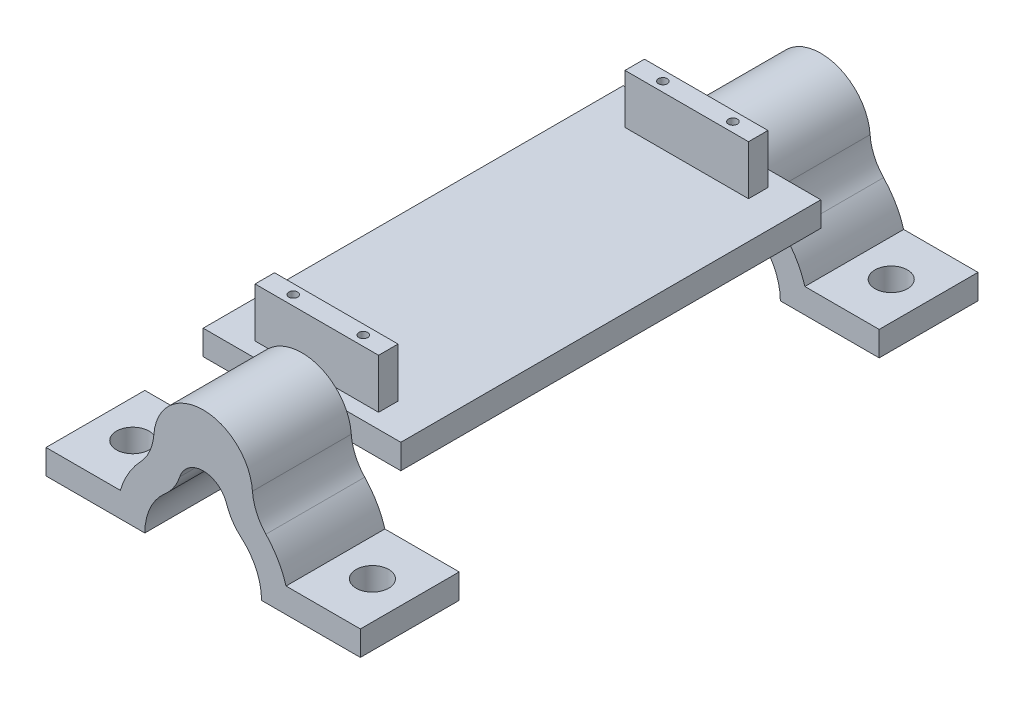
SolidWorks part; units mm, degrees
ref_plane "Front Plane" through (0, 0, 0) normal (0, 0, 1) x (1, 0, 0)
ref_plane "Top Plane" through (0, 0, 0) normal (0, 1, 0) x (1, 0, 0)
ref_plane "Right Plane" through (0, 0, 0) normal (1, 0, 0) x (0, 0, -1)
sketch "Sketch1" plane through (0, 0, 0) normal (0, 0, 1) x (1, 0, 0)
  line L2 (-40.4, 0) -> (-15, 0)
  line L5 (-21.2985, 6.35) -> (-40.4, 6.35)
  line L6 (-40.4, 0) -> (-40.4, 6.35)
  line L12 (40.4, 0) -> (40.4, 6.35)
  line L13 (21.2985, 6.35) -> (40.4, 6.35)
  line L14 (15, 0) -> (40.4, 0)
  arc A0 (15, 0) -> (9.7945, 11.3608) centre (0, 0) ccw
  arc A1 (21.2985, 6.35) -> (16.1223, 15.2977) centre (0, 0) ccw
  arc A4 (12.6676, 23.1321) -> (-12.6676, 23.1321) centre (0, 22.225) ccw
  arc A5 (6.0291, 16.9932) -> (-6.0291, 16.9932) centre (0, 15) ccw
  arc A6 (-9.7945, 11.3608) -> (-15, 0) centre (0, 0) ccw
  arc A7 (-16.1223, 15.2977) -> (-21.2985, 6.35) centre (0, 0) ccw
  arc A8 (-12.6676, 23.1321) -> (-16.1223, 15.2977) centre (-25.3351, 24.0393) cw
  arc A9 (16.1223, 15.2977) -> (12.6676, 23.1321) centre (25.3351, 24.0393) cw
  arc A10 (-9.7945, 11.3608) -> (-6.0291, 16.9932) centre (-18.0872, 20.9796) ccw
  arc A11 (6.0291, 16.9932) -> (9.7945, 11.3608) centre (18.0872, 20.9796) ccw
  point P17 (-12.1706, 18.5964)
  point P23 (-6.2061, 13.6559)
  dimension "D1" = 30
  dimension "D2" = 44.45
  dimension "D5" = 12.7
  dimension "D6" = 12.7
  dimension "D7" = 12.7
  dimension "D8" = 12.7
  dimension "D3" = 25.4
  dimension "D4" = 6.35
extrude "Boss-Extrude1" add sketch "Sketch1" along normal blind 25.4
sketch "Sketch2" plane through (0, 6.35, 0) normal (0, 1, 0) x (1, 0, 0)
  line L0 (-21.2985, -25.4) -> (-40.4, -25.4) construction
  line L1 (-21.2985, -25.4) -> (-21.2985, 0) construction
  line L2 (21.2985, -25.4) -> (21.2985, 0) construction
  line L3 (40.4, -25.4) -> (21.2985, -25.4) construction
  circle A0 centre (-30.7985, -12.7) radius 4.191
  circle A1 centre (30.7986, -12.7) radius 4.191
  dimension "D1" = 8.382
  dimension "D2" = 12.7
  dimension "D3" = 9.5
  dimension "D4" = 8.382
  dimension "D5" = 9.5
  dimension "D6" = 12.7
extrude "Cut-Extrude1" cut sketch "Sketch2" against normal up to surface (6.35 mm away) up to face at (-27.7, 0, 12.7)
sketch "Sketch3" plane through (0, 0, 0) normal (0, 0, -1) x (-1, 0, 0)
  line L2 (-25.4, 21.35) -> (-25.4, 27.7)
  line L3 (-25.4, 21.35) -> (25.4, 21.35)
  line L5 (-25.4, 27.7) -> (25.4, 27.7)
  line L6 (25.4, 21.35) -> (25.4, 27.7)
  dimension "D1" = 50.8
  dimension "D2" = 6.35
extrude "Boss-Extrude2" add sketch "Sketch3" along normal blind 107.95
ref_plane "Plane1" through (0, 0, -53.975) normal (0, 0, -1) x (-1, 0, 0)
mirror "Mirror1" about plane through (0, 0, -53.975) normal (0, 0, -1) of "Cut-Extrude1", "Boss-Extrude1"
sketch "Sketch5" plane through (0, 27.7, 0) normal (0, 1, 0) x (1, 0, 0)
  line L0 (11.4592, 0) -> (25.4, 0) construction
  line L1 (15.875, 3.81) -> (-15.875, 3.81)
  line L2 (15.875, 3.81) -> (15.875, 8.81)
  line L3 (15.875, 8.81) -> (-15.875, 8.81)
  line L4 (-15.875, 3.81) -> (-15.875, 8.81)
  line L5 (15.875, 98.89) -> (-15.875, 98.89)
  line L6 (15.875, 98.89) -> (15.875, 103.89)
  line L7 (15.875, 103.89) -> (-15.875, 103.89)
  line L8 (-15.875, 98.89) -> (-15.875, 103.89)
  line L9 (25.4, 107.95) -> (25.4, 0) construction
  dimension "D1" = 3.81
  dimension "D2" = 5
  dimension "D3" = 5
  dimension "D4" = 100.08
  dimension "D5" = 31.75
  dimension "D6" = 31.75
  dimension "D7" = 9.525
  dimension "D8" = 9.525
extrude "Boss-Extrude3" add sketch "Sketch5" along normal blind 12.7
sketch "Sketch4" plane through (0, 27.7, 0) normal (0, 1, 0) x (1, 0, 0)
  line L0 (-11.4592, 0) -> (11.4592, 0) construction
  line L1 (25.4, 107.95) -> (25.4, 0) construction
  circle A0 centre (9.4, 101.35) radius 1.15
  circle A1 centre (-8.6, 101.35) radius 1.15
  circle A2 centre (9.4, 6.35) radius 1.15
  circle A3 centre (-8.6, 6.35) radius 1.15
  point P4 (-8.4196, 51.216)
  point P5 (-12.1036, 93.4577)
  dimension "D1" = 2.3
  dimension "D2" = 2.3
  dimension "D3" = 2.3
  dimension "D4" = 2.3
  dimension "D6" = 95
  dimension "D8" = 18
  dimension "D9" = 0
  dimension "D10" = 95
  dimension "D11" = 6.35
  dimension "D12" = 16
  dimension "D5" = 0
  dimension "D7" = 6.35
extrude "Cut-Extrude2" cut sketch "Sketch4" against normal through all both and the other way through all
